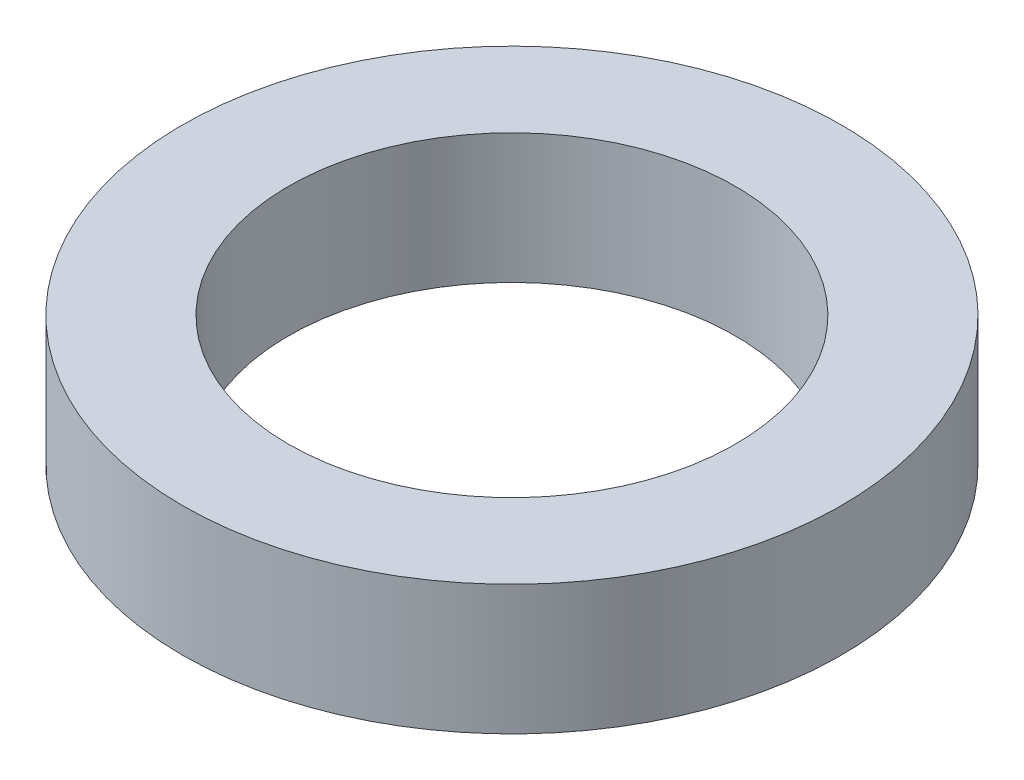
SolidWorks part; units mm, degrees
ref_plane "Front Plane" through (0, 0, 0) normal (0, 0, 1) x (1, 0, 0)
ref_plane "Top Plane" through (0, 0, 0) normal (0, 1, 0) x (1, 0, 0)
ref_plane "Right Plane" through (0, 0, 0) normal (1, 0, 0) x (0, 0, -1)
sketch "Sketch1" plane through (0, 0, 0) normal (0, 1, 0) x (1, 0, 0)
  circle A0 centre (0, 0) radius 5.08
  circle A1 centre (0, 0) radius 7.493
  dimension "D2" = 14.986
  dimension "D1" = 10.16
extrude "Boss-Extrude1" add sketch "Sketch1" along normal blind 2.9464
